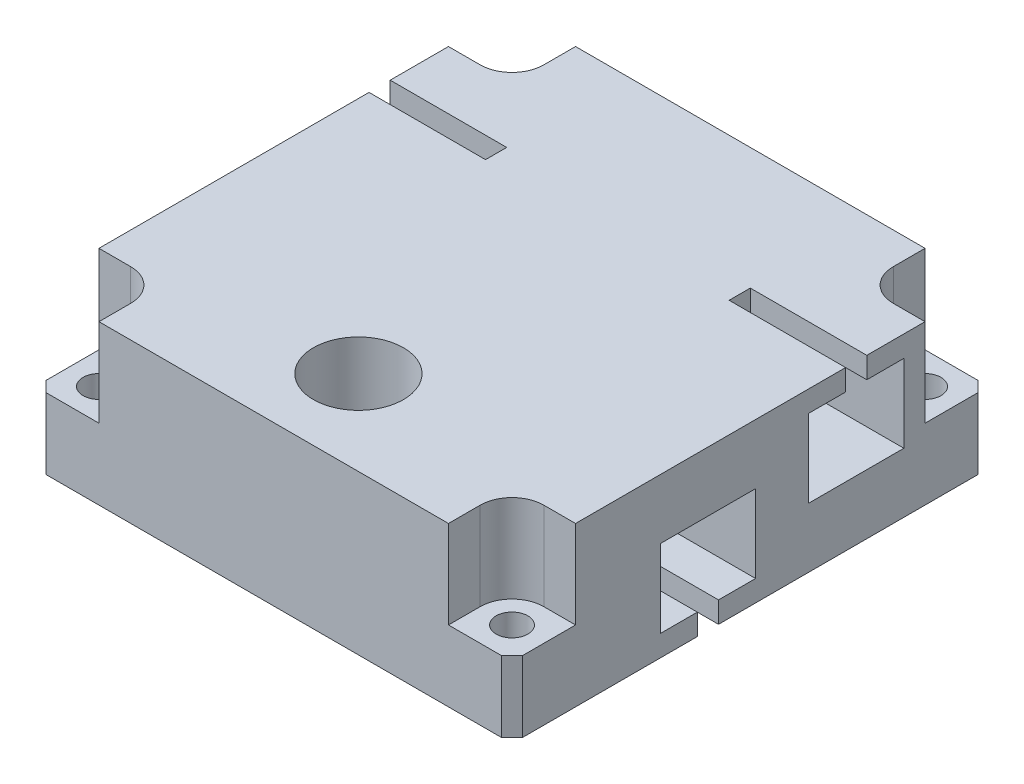
SolidWorks part; units mm, degrees
ref_plane "前视基准面" through (0, 0, 0) normal (0, 0, 1) x (1, 0, 0)
ref_plane "上视基准面" through (0, 0, 0) normal (0, 1, 0) x (1, 0, 0)
ref_plane "右视基准面" through (0, 0, 0) normal (1, 0, 0) x (0, 0, -1)
sketch "草图1" plane through (0, 0, 0) normal (0, 1, 0) x (1, 0, 0)
  line L1 (-22.5, -19.5) -> (22.5, -19.5)
  line L2 (-22.5, -19.5) -> (-22.5, 19.5)
  line L3 (-22.5, 19.5) -> (22.5, 19.5)
  line L4 (22.5, -19.5) -> (22.5, 19.5)
  line L5 (-22.5, -19.5) -> (22.5, 19.5) construction
  line L6 (-22.5, 19.5) -> (22.5, -19.5) construction
  point P0 (0, 0)
  dimension "D1" = 45
  dimension "D2" = 39
extrude "凸台-拉伸1" add sketch "草图1" along normal blind 15
sketch "草图2" plane through (-22.5, 0, 0) normal (-1, 0, 0) x (0, 0, 1)
  line L0 (0, 15) -> (0, 0) construction
  line L1 (-19.5, 15) -> (19.5, 15) construction
  line L2 (-7, 15) -> (-7, 0) construction
  line L3 (-19.5, 0) -> (19.5, 0) construction
  line L5 (-8, 13) -> (-8, 15)
  line L6 (-11.5, 13) -> (-8, 13)
  line L7 (-11.5, 13) -> (-11.5, 5.65)
  line L8 (-11.5, 5.65) -> (-2.5, 5.65)
  line L9 (-2.5, 13) -> (-2.5, 5.65)
  line L10 (-11.5, 13) -> (-2.5, 5.65) construction
  line L11 (-11.5, 5.65) -> (-2.5, 13) construction
  line L12 (-8, 15) -> (-6, 15)
  line L13 (-6, 13) -> (-6, 15)
  line L14 (-6, 13) -> (-2.5, 13)
  line L15 (-7, 9.325) -> (0, 9.325) construction
  line L16 (7, 15) -> (7, 0) construction
  line L17 (6, 2) -> (6, 0)
  line L18 (2.5, 2) -> (6, 2)
  line L19 (2.5, 2) -> (2.5, 9.35)
  line L20 (2.5, 9.35) -> (11.5, 9.35)
  line L21 (11.5, 2) -> (11.5, 9.35)
  line L22 (2.5, 2) -> (11.5, 9.35) construction
  line L23 (2.5, 9.35) -> (11.5, 2) construction
  line L24 (6, 0) -> (8, 0)
  line L25 (7, 5.675) -> (0, 5.675) construction
  line L26 (8, 2) -> (8, 0)
  line L27 (8, 2) -> (11.5, 2)
  point P11 (-7, 9.325)
  point P24 (7, 5.675)
  dimension "D2" = 7.35
  dimension "D3" = 9
  dimension "D4" = 1
  dimension "D5" = 2
  dimension "D6" = 9
  dimension "D7" = 7.35
  dimension "D8" = 7
  dimension "D9" = 1
  dimension "D10" = 2
  dimension "D11" = 7
extrude "切除-拉伸1" cut sketch "草图2" against normal blind 11
sketch "草图3" plane through (-11.5, 0, 0) normal (-1, 0, 0) x (0, 0, 1)
  line L0 (2.5, 2) -> (11.5, 9.35) construction
  circle A0 centre (-7, 9.325) radius 1.85
  circle A1 centre (7, 5.675) radius 1.85
  dimension "D1" = 3.7
  dimension "D2" = 3.7
extrude "切除-拉伸2" cut sketch "草图3" against normal blind 3
sketch "草图4" plane through (-8.5, 0, 0) normal (-1, 0, 0) x (0, 0, 1)
  circle A0 centre (-7, 9.325) radius 1.25
  circle A1 centre (7, 5.675) radius 1.25
  dimension "D1" = 2.5
  dimension "D2" = 2.5
extrude "切除-拉伸3" cut sketch "草图4" against normal through all
mirror "镜向1" about plane through (0, 0, 0) normal (1, 0, 0) of "切除-拉伸2", "切除-拉伸1"
sketch "草图5" plane through (0, 0, 0) normal (0, -1, 0) x (1, 0, 0)
  circle A0 centre (0, 0) radius 8
  dimension "D1" = 16
extrude "切除-拉伸4" cut sketch "草图5" against normal blind 12
sketch "草图6" plane through (0, 12, 0) normal (0, -1, 0) x (1, 0, 0)
  circle A0 centre (0, 0) radius 2.5
  dimension "D1" = 5
extrude "凸台-拉伸2" add sketch "草图6" along normal blind 1
sketch "草图7" plane through (0, 11, 0) normal (0, -1, 0) x (1, 0, 0)
  circle A0 centre (0, 0) radius 1.5
  dimension "D1" = 3
extrude "凸台-拉伸3" add sketch "草图7" along normal blind 1.8
sketch "草图8" plane through (0, 0, 19.5) normal (0, 0, 1) x (1, 0, 0)
  line L4 (-22.5, 0) -> (22.5, 0)
  line L5 (22.5, 0) -> (22.5, 15)
  line L6 (22.5, 15) -> (-22.5, 15)
  line L7 (-22.5, 15) -> (-22.5, 0)
  line L8 (-22.5, 0) -> (22.5, 0)
  line L9 (22.5, 0) -> (22.5, 15)
  line L10 (22.5, 15) -> (-22.5, 15)
  line L11 (-22.5, 15) -> (-22.5, 0)
  dimension "D1" = 0
extrude "凸台-拉伸4" add sketch "草图8" along normal blind 6
sketch "草图9" plane through (0, 15, 0) normal (0, 1, 0) x (1, 0, 0)
  line L0 (-11.5, 7) -> (11.5, 7) construction
  line L1 (-11.5, 11.5) -> (-11.5, 2.5) construction
  line L2 (11.5, 11.5) -> (11.5, 2.5) construction
  line L3 (0, 0) -> (0, 19.5) construction
  line L4 (22.5, 19.5) -> (-22.5, 19.5) construction
  circle A3 centre (0, 0) radius 8 construction
  circle A4 centre (0, 0) radius 8 construction
sketch "草图10" plane through (0, 15, 0) normal (0, 1, 0) x (1, 0, 0)
  line L0 (22.5, 19.5) -> (-22.5, 19.5) construction
  line L3 (-22.5, 19.5) -> (-22.5, 8) construction
  line L6 (-22.5, -3) -> (22.5, -3) construction
  line L9 (-22.5, 6) -> (-22.5, -25.5) construction
  line L10 (22.5, -25.5) -> (22.5, 6) construction
  line L11 (0, 19.5) -> (0, -25.5) construction
  line L12 (22.5, -25.5) -> (-22.5, -25.5) construction
  circle A0 centre (-19.5, 16.5) radius 1.5
  circle A4 centre (19.5, 16.5) radius 1.5
  circle A5 centre (19.5, -22.5) radius 1.5
  circle A6 centre (-19.5, -22.5) radius 1.5
  dimension "D5" = 3
  dimension "D1" = 3
  dimension "D2" = 3
  dimension "D3" = 22.5
extrude "切除-拉伸5" cut sketch "草图10" against normal through all
sketch "草图11" plane through (0, 15, 0) normal (0, 1, 0) x (1, 0, 0)
  line L10 (-16.5, 16.5) -> (-16.5, 19.5)
  line L11 (22.5, 19.5) -> (-22.5, 19.5) construction
  line L12 (-16.5, 19.5) -> (-22.5, 19.5)
  line L13 (-22.5, 19.5) -> (-22.5, 13.5)
  line L14 (-22.5, 13.5) -> (-19.5, 13.5)
  line L15 (0, 19.5) -> (0, -25.5) construction
  line L16 (22.5, -25.5) -> (-22.5, -25.5) construction
  line L17 (-22.5, -3) -> (22.5, -3) construction
  line L18 (-22.5, 6) -> (-22.5, -25.5) construction
  line L19 (22.5, 19.5) -> (22.5, 13.5)
  line L20 (16.5, 19.5) -> (22.5, 19.5)
  line L21 (16.5, 16.5) -> (16.5, 19.5)
  line L22 (22.5, 13.5) -> (19.5, 13.5)
  line L23 (16.5, -25.5) -> (22.5, -25.5)
  line L36 (16.5, -22.5) -> (16.5, -25.5)
  line L37 (22.5, -19.5) -> (19.5, -19.5)
  line L38 (22.5, -25.5) -> (22.5, -19.5)
  line L39 (-22.5, -25.5) -> (-22.5, -19.5)
  line L40 (-16.5, -25.5) -> (-22.5, -25.5)
  line L41 (-16.5, -22.5) -> (-16.5, -25.5)
  line L42 (-22.5, -19.5) -> (-19.5, -19.5)
  arc A4 (-19.5, 13.5) -> (-16.5, 16.5) centre (-19.5, 16.5) ccw
  arc A5 (19.5, 13.5) -> (16.5, 16.5) centre (19.5, 16.5) cw
  arc A6 (19.5, -19.5) -> (16.5, -22.5) centre (19.5, -22.5) ccw
  arc A8 (-19.5, -19.5) -> (-16.5, -22.5) centre (-19.5, -22.5) cw
  dimension "D1" = 3
  dimension "D2" = 22.5
extrude "切除-拉伸6" cut sketch "草图11" against normal blind 8.3
sketch "草图12" plane through (0, 0, 0) normal (0, -1, 0) x (1, 0, 0)
  line L0 (0, 25.5) -> (0, 17.5) construction
  line L1 (-22.5, 25.5) -> (22.5, 25.5) construction
  line L2 (0, 17.5) -> (-22.5, 17.5) construction
  line L3 (-22.5, 8) -> (-22.5, 25.5) construction
  circle A0 centre (0, 17.5) radius 4.25
  dimension "D1" = 8
  dimension "D2" = 8.5
extrude "切除-拉伸7" cut sketch "草图12" against normal through all
chamfer "倒角4" distance 2 angle 45 1 edges at (0, 0, 13.25)
chamfer "倒角2" distance 0.5 angle 45 1 edges at (0, 9.2, -1.5)
chamfer "倒角3" distance 1 angle 45 4 edges at (22.5, 3.35, 25.5) (22.5, 3.35, -19.5) (-22.5, 3.35, 25.5) (-22.5, 3.35, -19.5)
